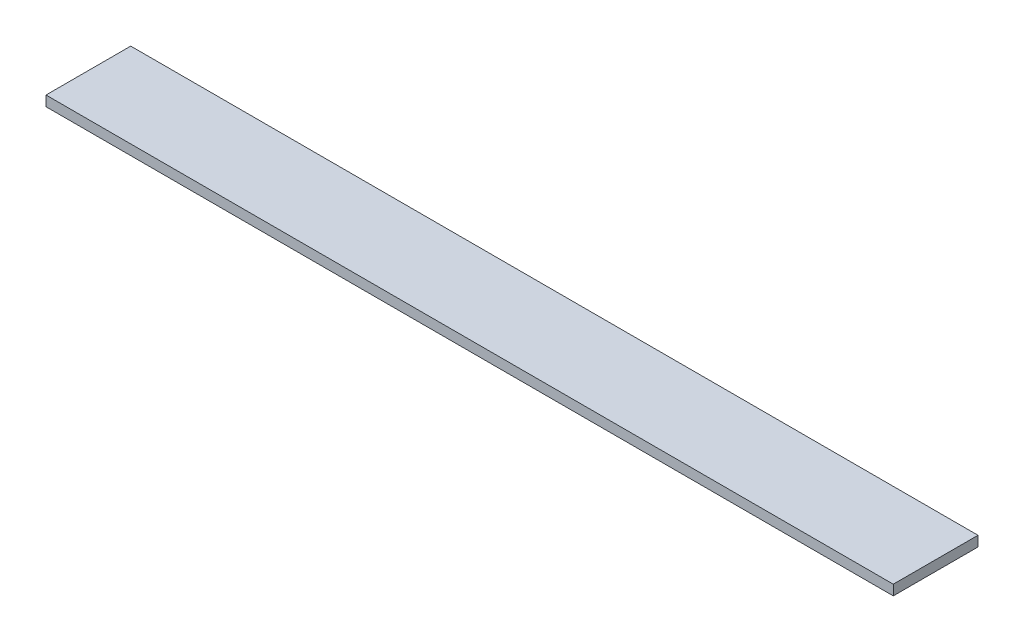
SolidWorks part; units mm, degrees
material "0.6015 (EN-GJL-150)"
ref_plane "Piano frontale" through (0, 0, 0) normal (0, 0, 1) x (1, 0, 0)
ref_plane "Piano superiore" through (0, 0, 0) normal (0, 1, 0) x (1, 0, 0)
ref_plane "Piano destro" through (0, 0, 0) normal (1, 0, 0) x (0, 0, -1)
sketch "Schizzo1" plane through (0, 0, 0) normal (0, 1, 0) x (1, 0, 0)
  line L1 (0, 0) -> (2500, 0)
  line L2 (0, 0) -> (0, 250)
  line L3 (0, 250) -> (2500, 250)
  line L4 (2500, 0) -> (2500, 250)
  dimension "D1" = 2500
  dimension "D2" = 250
extrude "Estrusione-Estrusione1" add sketch "Schizzo1" along normal blind 30
